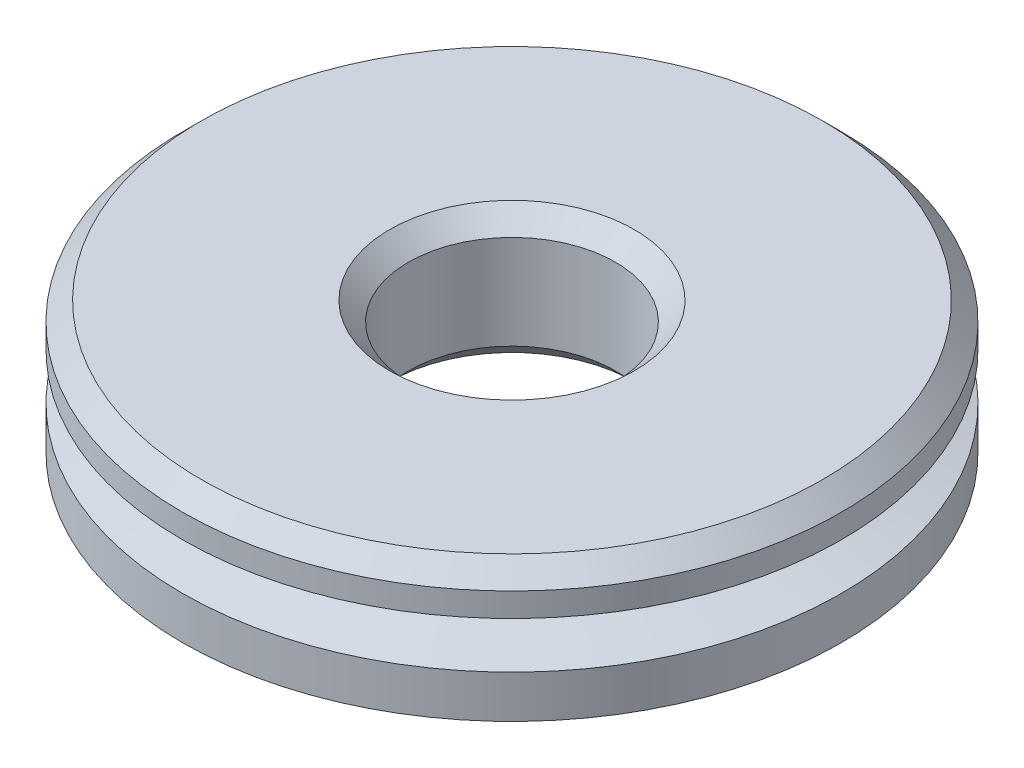
SolidWorks part; units mm, degrees
ref_plane "Front Plane" through (0, 0, 0) normal (0, 0, 1) x (1, 0, 0)
ref_plane "Top Plane" through (0, 0, 0) normal (0, 1, 0) x (1, 0, 0)
ref_plane "Right Plane" through (0, 0, 0) normal (1, 0, 0) x (0, 0, -1)
sketch "Sketch1" plane through (0, 0, 0) normal (0, 0, 1) x (1, 0, 0)
  line L0 (0, 0) -> (25.4, 0)
  line L3 (25.4, 12.7) -> (0, 12.7)
  line L4 (0, 12.7) -> (0, 0)
  line L5 (25.4, 12.7) -> (25.4, 11.43)
  line L6 (25.4, 11.43) -> (15.5976, 8.8035)
  line L7 (15.5976, 3.8965) -> (25.4, 1.27)
  line L8 (25.4, 1.27) -> (25.4, 0)
  line L9 (16.255, 6.35) -> (0, 6.35) construction
  line L10 (-16.51, 12.7) -> (-16.51, 0)
  arc A0 (15.5976, 8.8035) -> (15.5976, 3.8965) centre (16.255, 6.35) ccw
  dimension "D5" = 2.54
  dimension "D1" = 30
  dimension "D2" = 25.4
  dimension "D3" = 25.4
  dimension "D4" = 12.7
  dimension "D6" = 1.27
  dimension "D7" = 1.27
  dimension "D8" = 16.51
revolve "Revolve-Thin2" add sketch "Sketch1" angle 360 about L10
chamfer "Chamfer2" distance 2.54 3 edges at (-16.51, 15.24, 44.45) (-16.51, 15.24, 13.97) (-16.51, -2.54, 13.97)
